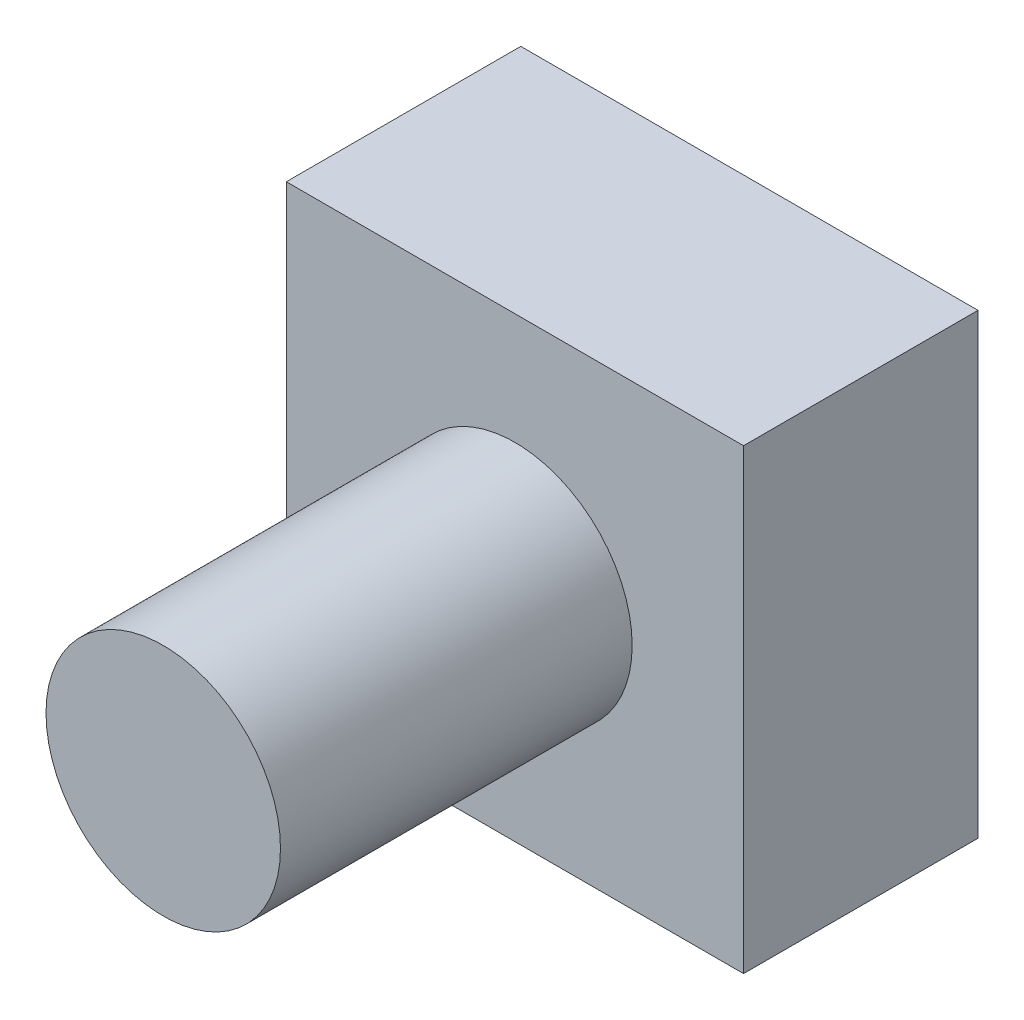
SolidWorks part; units mm, degrees
material "Dummy camera v5"
ref_plane "Front Plane" through (0, 0, 0) normal (0, 0, 1) x (1, 0, 0)
ref_plane "Top Plane" through (0, 0, 0) normal (0, 1, 0) x (1, 0, 0)
ref_plane "Right Plane" through (0, 0, 0) normal (1, 0, 0) x (0, 0, -1)
sketch "Body sketch" plane through (0, 0, 0) normal (0, 0, 1) x (1, 0, 0)
  line L1 (0, 0) -> (78, 0)
  line L2 (0, 0) -> (0, 78)
  line L3 (0, 78) -> (78, 78)
  line L4 (78, 0) -> (78, 78)
extrude "Body" add sketch "Body sketch" along normal blind 40
ref_plane "Top face plane" through (0, 0, 40) normal (0, 0, 1) x (1, 0, 0)
sketch "Boss sketch" plane through (0, 0, 40) normal (0, 0, 1) x (1, 0, 0)
  circle A0 centre (39, 39) radius 20
extrude "Boss" add sketch "Boss sketch" along normal blind 60
